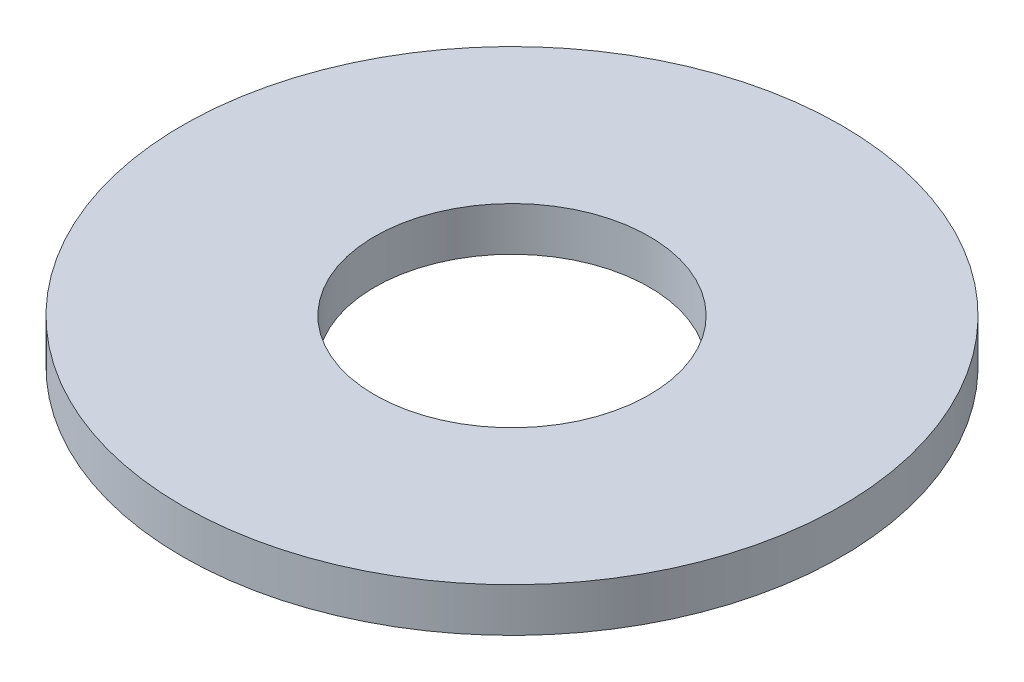
SolidWorks part; units mm, degrees
material "201 Annealed Stainless Steel (SS)"
ref_plane "Front Plane" through (0, 0, 0) normal (0, 0, 1) x (1, 0, 0)
ref_plane "Top Plane" through (0, 0, 0) normal (0, 1, 0) x (1, 0, 0)
ref_plane "Right Plane" through (0, 0, 0) normal (1, 0, 0) x (0, 0, -1)
sketch "Sketch1" plane through (0, 0, 0) normal (0, 1, 0) x (1, 0, 0)
  circle A0 centre (0, 0) radius 7.9375
  circle A1 centre (0, 0) radius 19.05
  dimension "D1" = 15.875
  dimension "D2" = 38.1
extrude "Boss-Extrude1" add sketch "Sketch1" along normal blind 2.54
